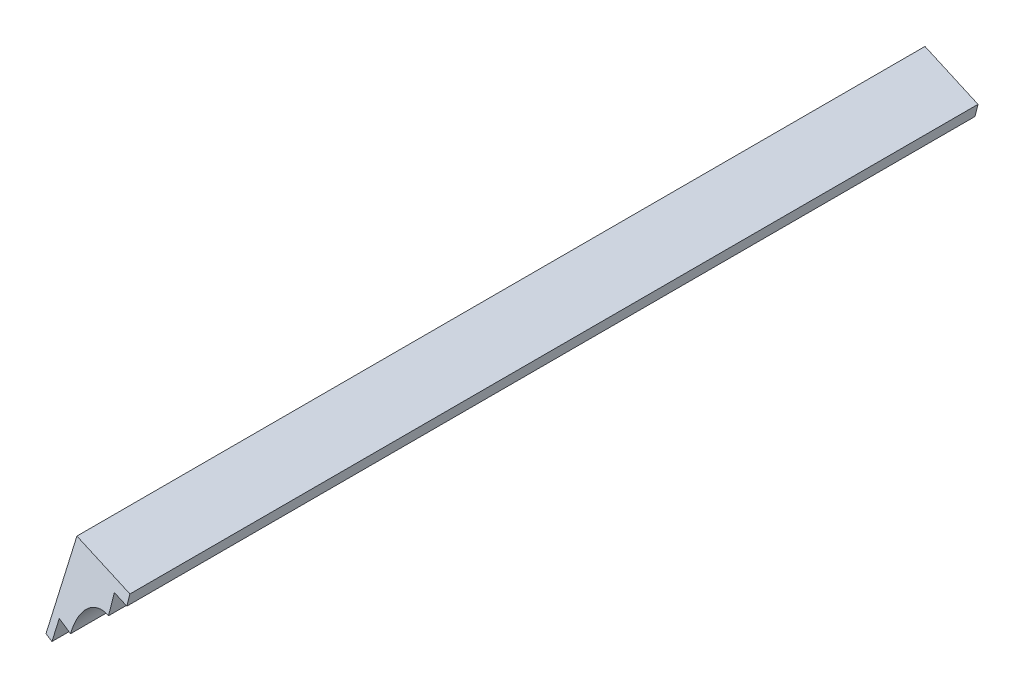
SolidWorks part; units mm, degrees
material "PET"
ref_plane "Front Plane" through (0, 0, 0) normal (0, 0, 1) x (1, 0, 0)
ref_plane "Top Plane" through (0, 0, 0) normal (0, 1, 0) x (1, 0, 0)
ref_plane "Right Plane" through (0, 0, 0) normal (1, 0, 0) x (0, 0, -1)
sketch "Sketch1" plane through (0, 0, 0) normal (0, 0, 1) x (1, 0, 0)
  line L0 (14.4048, 5.1784) -> (14.4048, 14.7084)
  line L1 (14.4048, 14.7084) -> (24.4048, 14.7084)
  line L2 (24.4048, 14.7084) -> (24.4048, 19.7084)
  line L3 (24.4048, 19.7084) -> (-17.9164, 19.7084)
  line L4 (-17.9164, 19.7084) -> (-21.9387, -22.4212)
  line L5 (-21.9387, -22.4212) -> (-16.9613, -22.8964)
  line L6 (-16.9613, -22.8964) -> (-16.0109, -12.9417)
  line L7 (-16.0109, -12.9417) -> (-6.524, -13.8474)
  line L10 (591.0708, 15.2011) -> (-13.8189, 15.2011) construction
  line L11 (579.8088, -637.8023) -> (17.6924, -19.4621) construction
  line L12 (-13.8189, 15.2011) -> (-71.309, -586.9505) construction
  arc A0 (14.4048, 5.1784) -> (-6.524, -13.8474) centre (13.4533, -14.7989) ccw construction
  arc A1 (14.4048, 5.1784) -> (-6.524, -13.8474) centre (13.4533, -14.7989) ccw
  dimension "D1" = 9.53
  dimension "D2" = 10
  dimension "D3" = 5
extrude "Boss-Extrude2" add sketch "Sketch1" along normal blind 514 and the other way blind 40
sketch "Sketch2" plane through (-738.2019, 812.0382, 3415.5611) normal (0.0908, 0.9513, -0.2946) x (-0.9556, 0, -0.2946)
  line L0 (69.8848, -3135.6099) -> (246.8241, -3135.6099)
  line L1 (148.9959, -3135.6099) -> (-148.9959, -3135.6099) construction
  line L2 (246.8241, -3135.6099) -> (167.6054, -3034.4341)
  line L3 (167.6054, -3034.4341) -> (69.8848, -3135.6099)
  line L4 (236.2622, -3561.3072) -> (313.7803, -3654.4039)
  line L5 (-316.4912, -3561.3072) -> (316.4912, -3561.3072) construction
  line L6 (313.7803, -3654.4039) -> (393.9087, -3561.3072)
  line L7 (393.9087, -3561.3072) -> (236.2622, -3561.3072)
  line L8 (-316.4912, -3561.3072) -> (316.4912, -3561.3072) construction
extrude "Cut-Extrude1" cut sketch "Sketch2" against normal through all both and the other way through all
